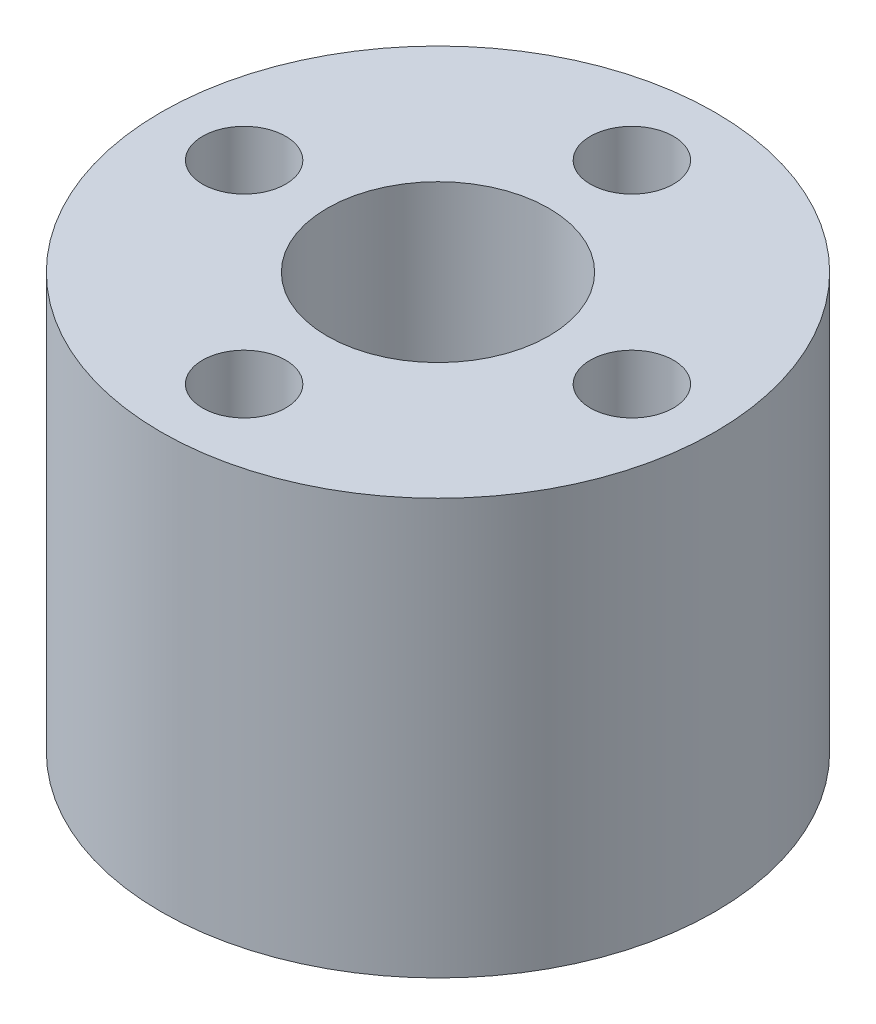
SolidWorks part; units mm, degrees
ref_plane "前视基准面" through (0, 0, 0) normal (0, 0, 1) x (1, 0, 0)
ref_plane "上视基准面" through (0, 0, 0) normal (0, 1, 0) x (1, 0, 0)
ref_plane "右视基准面" through (0, 0, 0) normal (1, 0, 0) x (0, 0, -1)
other "Configuration Table"
sketch "草图1" plane through (0, 0, 0) normal (0, 1, 0) x (1, 0, 0)
  line L0 (0, 0) -> (7, 0)
  line L1 (0, 0) -> (0, -7)
  line L2 (0, 0) -> (-7, 0)
  line L3 (0, 0) -> (0, 7)
  circle A0 centre (0, 7) radius 1.5
  circle A1 centre (-7, 0) radius 1.5
  circle A2 centre (0, -7) radius 1.5
  circle A3 centre (7, 0) radius 1.5
  circle A4 centre (0, 0) radius 4
  circle A5 centre (0, 0) radius 10
  dimension "D5" = 3
  dimension "D6" = 3
  dimension "D7" = 3
  dimension "D8" = 3
  dimension "D9" = 8
  dimension "D10" = 20
  dimension "D1" = 7
  dimension "D2" = 7
  dimension "D3" = 7
  dimension "D4" = 7
extrude "凸台-拉伸1" add sketch "草图1" along normal blind 15
